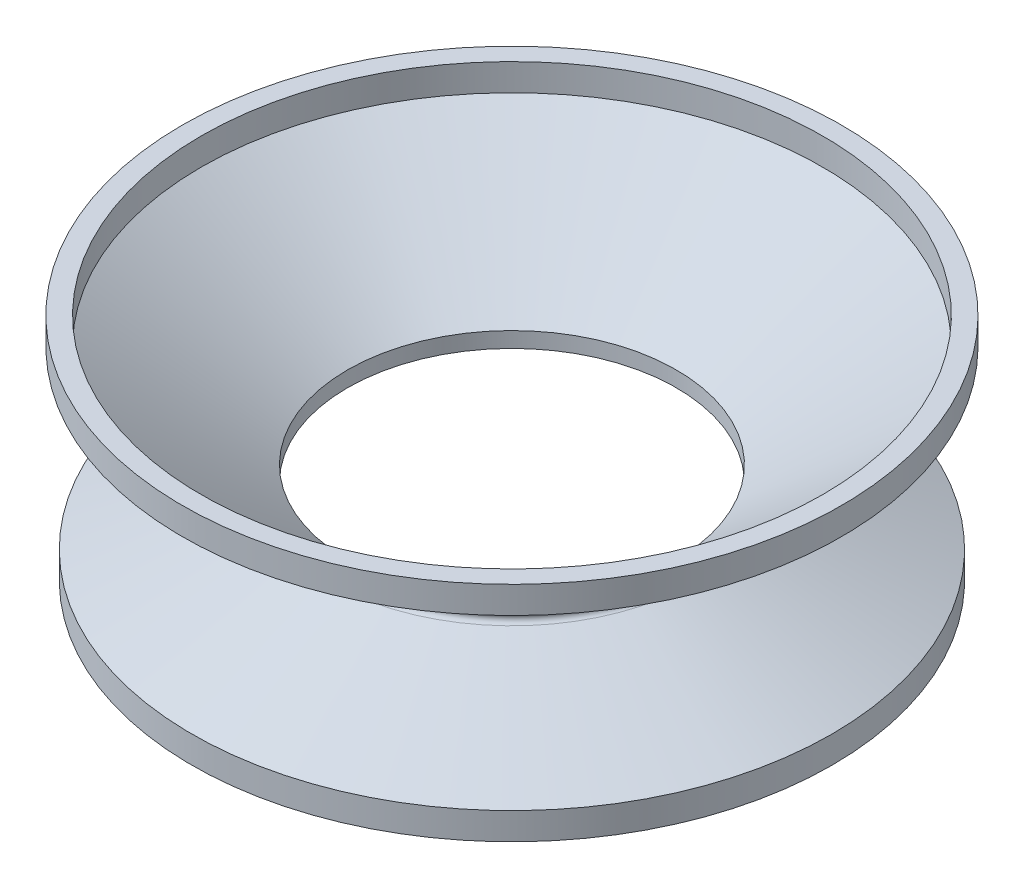
SolidWorks part; units mm, degrees
ref_plane "Front Plane" through (0, 0, 0) normal (0, 0, 1) x (1, 0, 0)
ref_plane "Top Plane" through (0, 0, 0) normal (0, 1, 0) x (1, 0, 0)
ref_plane "Right Plane" through (0, 0, 0) normal (1, 0, 0) x (0, 0, -1)
sketch "Sketch1" plane through (0, 0, 0) normal (0, 0, 1) x (1, 0, 0)
  line L0 (-42.6436, 0) -> (43.9692, 0) construction
  line L1 (0.6628, 0) -> (-10.7624, 8)
  line L2 (0.6628, 0) -> (-10.0598, -5)
  line L3 (1.4628, -0.7303) -> (-7.6936, -5)
  line L5 (-10.7624, 8) -> (-9.3676, 8)
  line L6 (-10.0598, -5) -> (-7.6936, -5)
  line L7 (13.6324, 7.609) -> (13.6324, -7.609) construction
  line L8 (2.6552, -0.1743) -> (-17.679, 14.0639) construction
  line L9 (0.6628, 0) -> (-18.2526, 13.2447) construction
  line L10 (0.6628, 0) -> (-18.8539, -9.1008) construction
  line L11 (2.6552, -0.1743) -> (-18.4313, -10.0071) construction
  line L12 (0.6628, 0) -> (2.2628, 0) construction
  line L13 (1.4628, -0.7303) -> (1.4628, 0.4165)
  line L14 (1.4628, 0.4165) -> (-9.3676, 8)
  point P11 (1.4628, 0)
  dimension "D1" = 35
  dimension "D2" = 25
  dimension "D4" = 8
  dimension "D5" = 5
  dimension "D6" = 23
  dimension "D7" = 1.6
  dimension "D8" = 0.8
  dimension "D3" = 1
revolve "Revolve1" add sketch "Sketch1" angle 360 about L7
scale "Scale1" [suppressed]
fillet "Fillet2" radius 0.4 1 edges at (0.6628, 0, 0)
sketch "Sketch2" plane through (0, 8, 0) normal (0, 1, 0) x (1, 0, 0)
  circle A0 centre (13.6324, 0) radius 24.3948 construction
  circle A1 centre (13.6324, 0) radius 23 construction
  circle A2 centre (13.6324, 0) radius 24.3948
  circle A3 centre (13.6324, 0) radius 23
extrude "Boss-Extrude1" add sketch "Sketch2" along normal blind 2
sketch "Sketch3" plane through (0, -5, 0) normal (0, -1, 0) x (1, 0, 0)
  circle A0 centre (13.6324, 0) radius 21.3259 construction
  circle A1 centre (13.6324, 0) radius 23.6921 construction
  circle A2 centre (13.6324, 0) radius 21.3259
  circle A3 centre (13.6324, 0) radius 23.6921
extrude "Boss-Extrude2" add sketch "Sketch3" along normal blind 2
